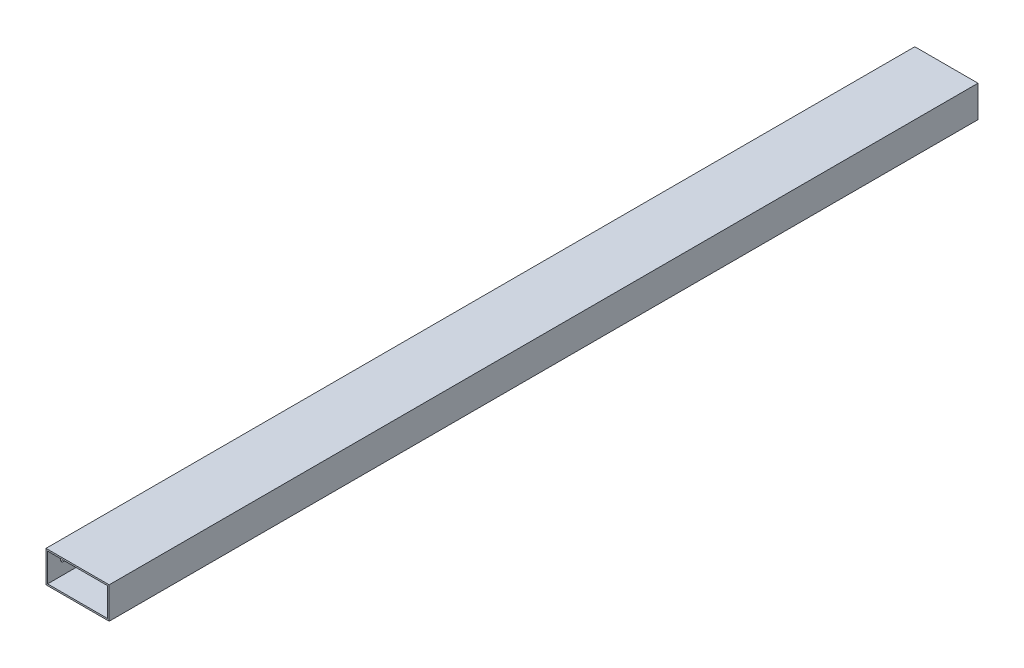
SolidWorks part; units mm, degrees
material "1060 合金"
ref_plane "前视基准面" through (0, 0, 0) normal (0, 0, 1) x (1, 0, 0)
ref_plane "上视基准面" through (0, 0, 0) normal (0, 1, 0) x (1, 0, 0)
ref_plane "右视基准面" through (0, 0, 0) normal (1, 0, 0) x (0, 0, -1)
other "Configuration Table"
sketch "草图1" plane through (0, 0, 0) normal (0, 0, 1) x (1, 0, 0)
  line L1 (0, 0) -> (40, 0)
  line L2 (0, 0) -> (0, -20)
  line L3 (0, -20) -> (40, -20)
  line L4 (40, 0) -> (40, -20)
  dimension "D1" = 20
  dimension "D2" = 40
extrude "拉伸-薄壁1" add sketch "草图1" along normal blind 550 thin
sketch "草图4" plane through (0, 0, 0) normal (-1, 0, 0) x (0, 0, 1)
  line L0 (550, 0) -> (0, 0) construction
  line L1 (550, 0) -> (550, -20) construction
  line L4 (0, -180.2783) -> (0, 689.7217) construction
  circle A1 centre (539.9964, -10) radius 1.75
  circle A49 centre (10, -10) radius 1.75
  dimension "D27" = 3.5
  dimension "D28" = 3.5
  dimension "D29" = 10
  dimension "D25" = 10
  dimension "D26" = 10.0036
  dimension "D30" = 10
extrude "切除-拉伸2" cut sketch "草图4" against normal blind 1.5
sketch "草图5" plane through (0, 0, 0) normal (-1, 0, 0) x (0, 0, 1)
  circle A0 centre (42.5, -10) radius 1.75 construction
  circle A1 centre (42.5, -10) radius 1.75
  circle A2 centre (62.5, -10) radius 1.75
  circle A3 centre (82.5, -10) radius 1.75
  circle A4 centre (102.5, -10) radius 1.75
  circle A5 centre (122.5, -10) radius 1.75
  circle A6 centre (142.5, -10) radius 1.75
  circle A7 centre (162.5, -10) radius 1.75
  circle A8 centre (182.5, -10) radius 1.75
  circle A9 centre (202.5, -10) radius 1.75
  circle A10 centre (222.5, -10) radius 1.75
  circle A11 centre (242.5, -10) radius 1.75
  circle A12 centre (262.5, -10) radius 1.75
  circle A13 centre (282.5, -10) radius 1.75
  circle A14 centre (302.5, -10) radius 1.75
  circle A15 centre (322.5, -10) radius 1.75
  circle A16 centre (342.5, -10) radius 1.75
  circle A17 centre (362.5, -10) radius 1.75
  circle A18 centre (382.5, -10) radius 1.75
  circle A19 centre (402.5, -10) radius 1.75
  circle A20 centre (422.5, -10) radius 1.75
  circle A21 centre (442.5, -10) radius 1.75
  circle A22 centre (462.5, -10) radius 1.75
  circle A23 centre (482.5, -10) radius 1.75
  dimension "D1" = 23
sketch "草图6" plane through (40, 0, 0) normal (1, 0, 0) x (0, 0, -1)
  line L0 (-550, -20) -> (0, -20) construction
  line L1 (-550, -20) -> (-550, 0) construction
  circle A0 centre (-320, -10) radius 2.5
  circle A1 centre (-230, -10) radius 2.5
  dimension "D1" = 5
  dimension "D2" = 5
  dimension "D3" = 10
  dimension "D4" = 10
  dimension "D5" = 230
  dimension "D6" = 230
